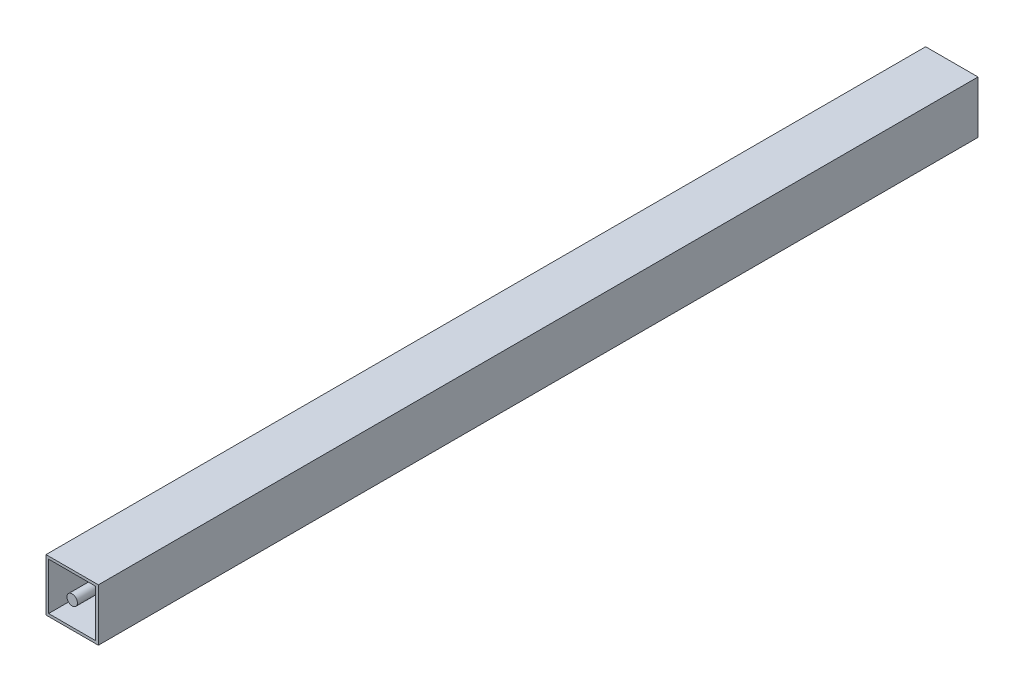
SolidWorks part; units mm, degrees
material "1060 Alloy"
ref_plane "Front" through (0, 0, 0) normal (0, 0, 1) x (1, 0, 0)
ref_plane "Top" through (0, 0, 0) normal (0, 1, 0) x (1, 0, 0)
ref_plane "Right" through (0, 0, 0) normal (1, 0, 0) x (0, 0, -1)
sketch "Sketch1" plane through (0, 0, 0) normal (0, 0, 1) x (1, 0, 0)
  line L1 (0, 0) -> (9, 0)
  line L2 (0, 0) -> (0, 9)
  line L3 (0, 9) -> (9, 9)
  line L4 (9, 0) -> (9, 9)
  line L5 (-0.5, 9.5) -> (9.5, 9.5)
  line L6 (-0.5, 9.5) -> (-0.5, -0.5)
  line L7 (-0.5, -0.5) -> (9.5, -0.5)
  line L8 (9.5, 9.5) -> (9.5, -0.5)
  line L9 (-0.5, 9.5) -> (9.5, -0.5) construction
  line L10 (-0.5, -0.5) -> (9.5, 9.5) construction
  circle A0 centre (4.5, 4.5) radius 1
  point P8 (4.5, 9)
  point P10 (0, 4.5)
  dimension "D3" = 2
  dimension "D1" = 9
  dimension "D2" = 9
  dimension "D4" = 0.5
  dimension "D5" = 0.5
extrude "Boss-Extrude1" add sketch "Sketch1" along normal blind 168 contours L8 L5 L6 L7 L4 L1 L2 L3 | A0
